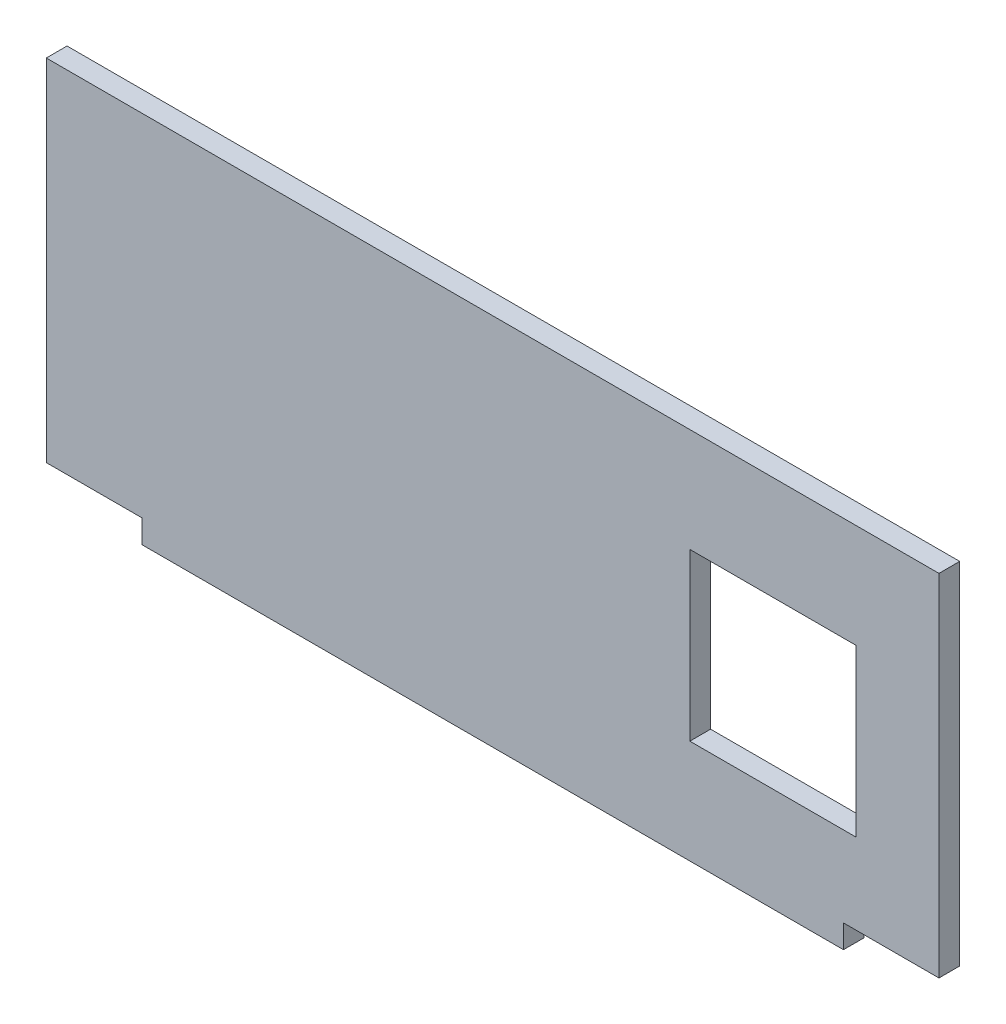
SolidWorks part; units mm, degrees
material "Balsa"
ref_plane "Plan de face" through (0, 0, 0) normal (0, 0, 1) x (1, 0, 0)
ref_plane "Plan de dessus" through (0, 0, 0) normal (0, 1, 0) x (1, 0, 0)
ref_plane "Plan de droite" through (0, 0, 0) normal (1, 0, 0) x (0, 0, -1)
sketch "Esquisse1" plane through (0, 0, 0) normal (0, 0, 1) x (1, 0, 0)
  line L1 (0, 0) -> (-430, 0)
  line L2 (0, 0) -> (0, 180)
  line L3 (0, 180) -> (-430, 180)
  line L4 (-430, 0) -> (-430, 180)
  dimension "D1" = 430
  dimension "D2" = 180
extrude "Boss.-Extru.1" add sketch "Esquisse1" along normal blind 10
sketch "Esquisse2" plane through (0, 0, 0) normal (0, 0, -1) x (-1, 0, 0)
  line L0 (0, 0) -> (0, 180) construction
  line L1 (40, 130) -> (120, 130)
  line L2 (40, 130) -> (40, 50)
  line L3 (40, 50) -> (120, 50)
  line L4 (120, 130) -> (120, 50)
  line L5 (430, 0) -> (0, 0) construction
  dimension "D1" = 80
  dimension "D2" = 80
  dimension "D3" = 40
  dimension "D4" = 50
extrude "Enlèv. mat.-Extru.1" cut sketch "Esquisse2" against normal blind 10
sketch "Esquisse4" plane through (0, 0, 10) normal (0, 0, 1) x (1, 0, 0)
  line L1 (0, 0) -> (-46, 0)
  line L2 (0, 0) -> (0, 11.2)
  line L3 (0, 11.2) -> (-46, 11.2)
  line L4 (-46, 0) -> (-46, 11.2)
  line L5 (-430, 0) -> (-384, 0)
  line L6 (-430, 0) -> (-430, 11.2)
  line L7 (-430, 11.2) -> (-384, 11.2)
  line L8 (-384, 0) -> (-384, 11.2)
  dimension "D1" = 46
  dimension "D2" = 11.2
  dimension "D3" = 46
  dimension "D4" = 11.2
extrude "Enlèv. mat.-Extru.2" cut sketch "Esquisse4" against normal blind 10
